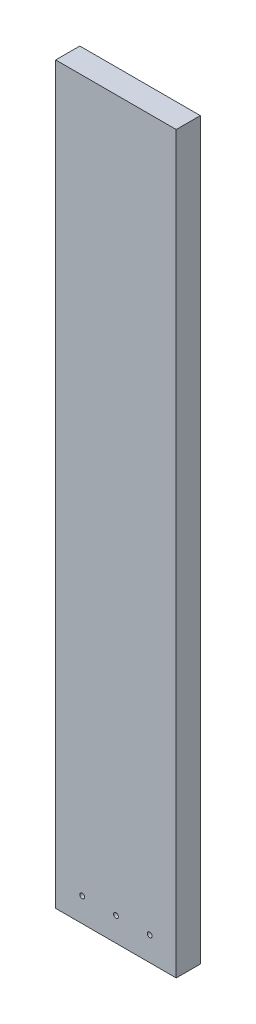
SolidWorks part; units mm, degrees
ref_plane "Front Plane" through (0, 0, 0) normal (0, 0, 1) x (1, 0, 0)
ref_plane "Top Plane" through (0, 0, 0) normal (0, 1, 0) x (1, 0, 0)
ref_plane "Right Plane" through (0, 0, 0) normal (1, 0, 0) x (0, 0, -1)
sketch "Sketch1" plane through (0, 0, 0) normal (0, 0, 1) x (1, 0, 0)
  line L0 (0, 199.5602) -> (0, -264.2102) construction
  line L1 (-25, 152.4) -> (25, 152.4)
  line L2 (-25, 152.4) -> (-25, -152.4)
  line L3 (-25, -152.4) -> (25, -152.4)
  line L4 (25, 152.4) -> (25, -152.4)
  line L5 (-45.1983, 0) -> (43.1762, 0) construction
  line L6 (-38.2115, -142.4) -> (39.2079, -142.4) construction
  line L7 (-14, -133.9217) -> (-14, -148.8474) construction
  line L8 (14, -133.9217) -> (14, -148.8474) construction
  circle A0 centre (-14, -142.4) radius 1
  circle A1 centre (0, -142.4) radius 1
  circle A2 centre (14, -142.4) radius 1
  dimension "D6" = 2
  dimension "D7" = 2
  dimension "D8" = 2
  dimension "D1" = 304.8
  dimension "D2" = 50
  dimension "D3" = 10
  dimension "D4" = 14
  dimension "D5" = 14
extrude "Boss-Extrude1" add sketch "Sketch1" along normal blind 10
